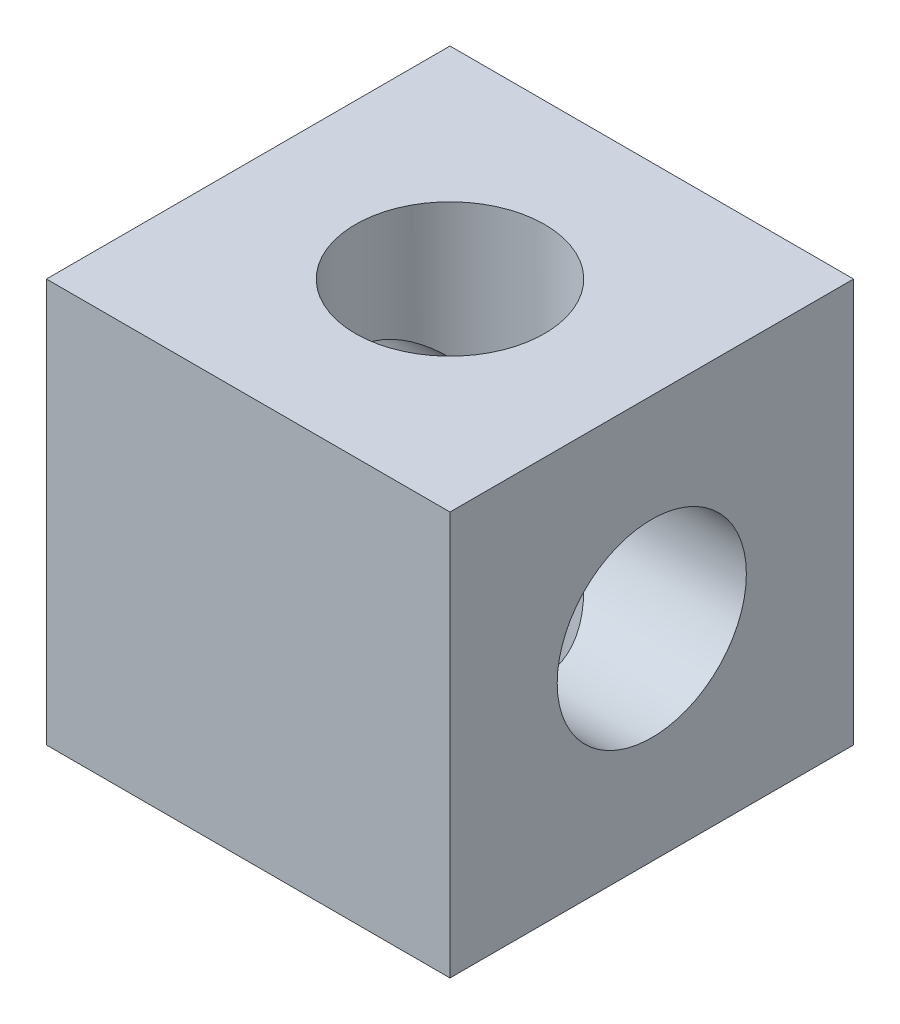
SolidWorks part; units mm, degrees
ref_plane "정면" through (0, 0, 0) normal (0, 0, 1) x (1, 0, 0)
ref_plane "윗면" through (0, 0, 0) normal (0, 1, 0) x (1, 0, 0)
ref_plane "우측면" through (0, 0, 0) normal (1, 0, 0) x (0, 0, -1)
ref_plane "평면1" through (10.16, 0, 0) normal (1, 0, 0) x (0, 0, -1)
sketch "스케치1" plane through (10.16, 0, 0) normal (1, 0, 0) x (0, 0, -1)
  line L0 (-10.16, -10.16) -> (10.16, -10.16)
  line L1 (10.16, -10.16) -> (10.16, 10.16)
  line L2 (10.16, 10.16) -> (-10.16, 10.16)
  line L3 (-10.16, 10.16) -> (-10.16, -10.16)
extrude "보스-돌출1" add sketch "스케치1" against normal blind 20.32
hole_wizard "M8 여유 구멍1" positions "스케치3" profile "스케치2" hole size "M8" standard "Ansi Metric"
sketch "스케치3" plane through (-10.16, 0, 0) normal (-1, 0, 0) x (0, 0, 1)
  point P0 (0, 0)
sketch "스케치2" plane through (-10.16, 0, 0) normal (0, 1, 0) x (0, 0, 1)
  line L0 (0, 0) -> (0, 20.32)
  line L1 (0, 20.32) -> (4.7625, 20.32)
  line L2 (4.7625, 20.32) -> (4.7625, 0)
  line L5 (4.7625, 0) -> (0, 0)
  line L11 (0, -6.35) -> (0, 107.95) construction
  dimension "관통 구멍 지름" = 9.525
  dimension "관통 구멍 깊이" = 20.32
hole_wizard "M8 여유 구멍2" positions "스케치5" profile "스케치4" hole size "M8" standard "Ansi Metric"
sketch "스케치5" plane through (0, 10.16, 0) normal (0, 1, 0) x (1, 0, 0)
  point P0 (0, 0)
sketch "스케치4" plane through (0, 10.16, 0) normal (1, 0, 0) x (0, 0, 1)
  line L0 (0, 0) -> (0, 30.48)
  line L1 (0, 30.48) -> (4.7625, 30.48)
  line L2 (4.7625, 30.48) -> (4.7625, 0)
  line L5 (4.7625, 0) -> (0, 0)
  line L10 (0, 30.48) -> (-4.7625, 30.48) construction
  line L11 (0, -6.35) -> (0, 107.95) construction
  dimension "구멍 지름" = 9.525
  dimension "구멍 깊이" = 30.48
  dimension "드릴 각도" = 180
